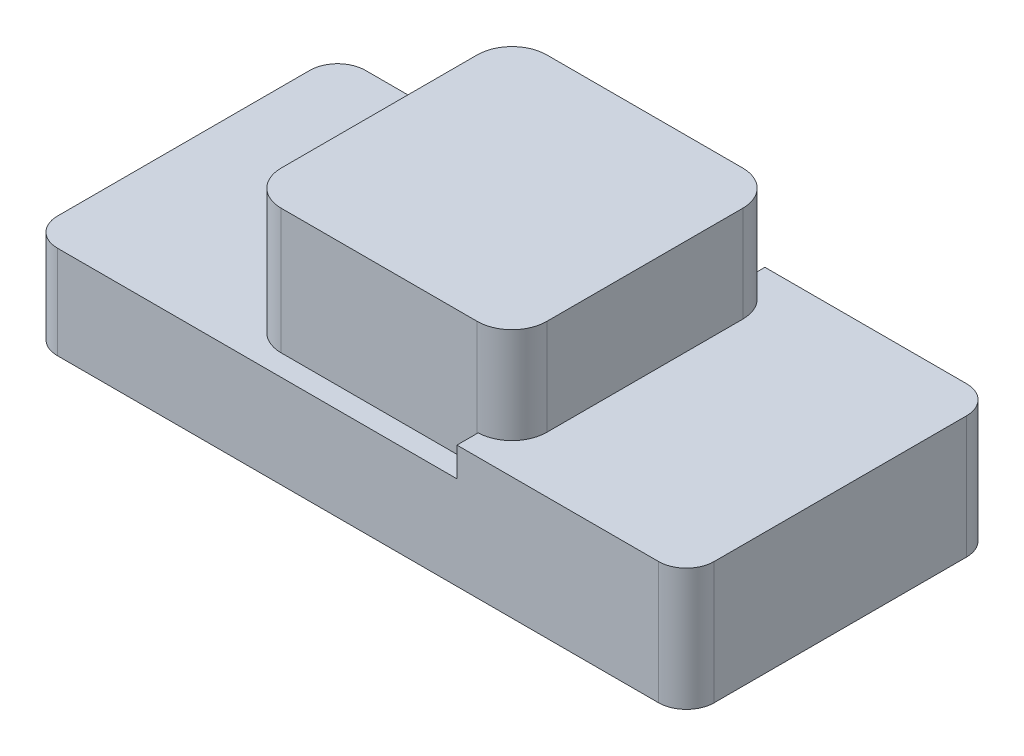
SolidWorks part; units mm, degrees
ref_plane "Front" through (0, 0, 0) normal (0, 0, 1) x (1, 0, 0)
ref_plane "Top" through (0, 0, 0) normal (0, 1, 0) x (1, 0, 0)
ref_plane "Right" through (0, 0, 0) normal (1, 0, 0) x (0, 0, -1)
sketch "Sketch1" plane through (0, 0, 0) normal (0, 0, 1) x (1, 0, 0)
  line L1 (0, 0) -> (-77.8583, 0)
  line L3 (-16.3983, 13.4) -> (-77.8583, 13.4)
  line L4 (-77.8583, 0) -> (-77.8583, 13.4)
  line L9 (0, 0) -> (16.6017, 0)
  line L10 (-16.3983, 13.4) -> (-16.3983, 17.6)
  line L11 (-16.3983, 17.6) -> (16.6017, 17.6)
  line L12 (16.6017, 0) -> (16.6017, 17.6)
  point P8 (-40.9692, 13.4)
  point P9 (0, 0)
  point P10 (0, 0)
  dimension "D1" = 13.4
  dimension "D2" = 17.6
  dimension "D3" = 94.46
  dimension "D4" = 33
extrude "Boss-Extrude1" add sketch "Sketch1" along normal blind 44.3
sketch "Sketch2" plane through (0, 13.4, 0) normal (0, 1, 0) x (1, 0, 0)
  line L0 (-77.8583, -22.15) -> (16.6017, -22.15) construction
  line L1 (-49.7283, -41.25) -> (-11.5283, -41.25)
  line L2 (-49.7283, -41.25) -> (-49.7283, -3.05)
  line L3 (-49.7283, -3.05) -> (-11.5283, -3.05)
  line L4 (-11.5283, -41.25) -> (-11.5283, -3.05)
  line L5 (-77.8583, -44.3) -> (-77.8583, 0) construction
  line L6 (16.6017, -44.3) -> (16.6017, 0) construction
  line L7 (-77.8583, 0) -> (16.6017, 0) construction
  line L8 (16.6017, 0) -> (-16.3983, 0) construction
  line L9 (16.6017, 0) -> (-30.6283, 0) construction
  line L10 (-30.6283, 0) -> (-30.6283, -44.3) construction
  line L11 (-16.3983, -44.3) -> (-77.8583, -44.3) construction
  dimension "D1" = 38.2
  dimension "D2" = 38.2
extrude "Boss-Extrude2" add sketch "Sketch2" along normal blind 18.02
fillet "Fillet1" radius 5 4 edges at (-49.7283, 22.41, 3.05) (-11.5283, 24.51, 3.05) (-11.5283, 24.51, 41.25) (-49.7283, 22.41, 41.25)
fillet "Fillet2" radius 4 4 edges at (-77.8583, 6.7, 0) (16.6017, 8.8, 0) (16.6017, 8.8, 44.3) (-77.8583, 6.7, 44.3)
